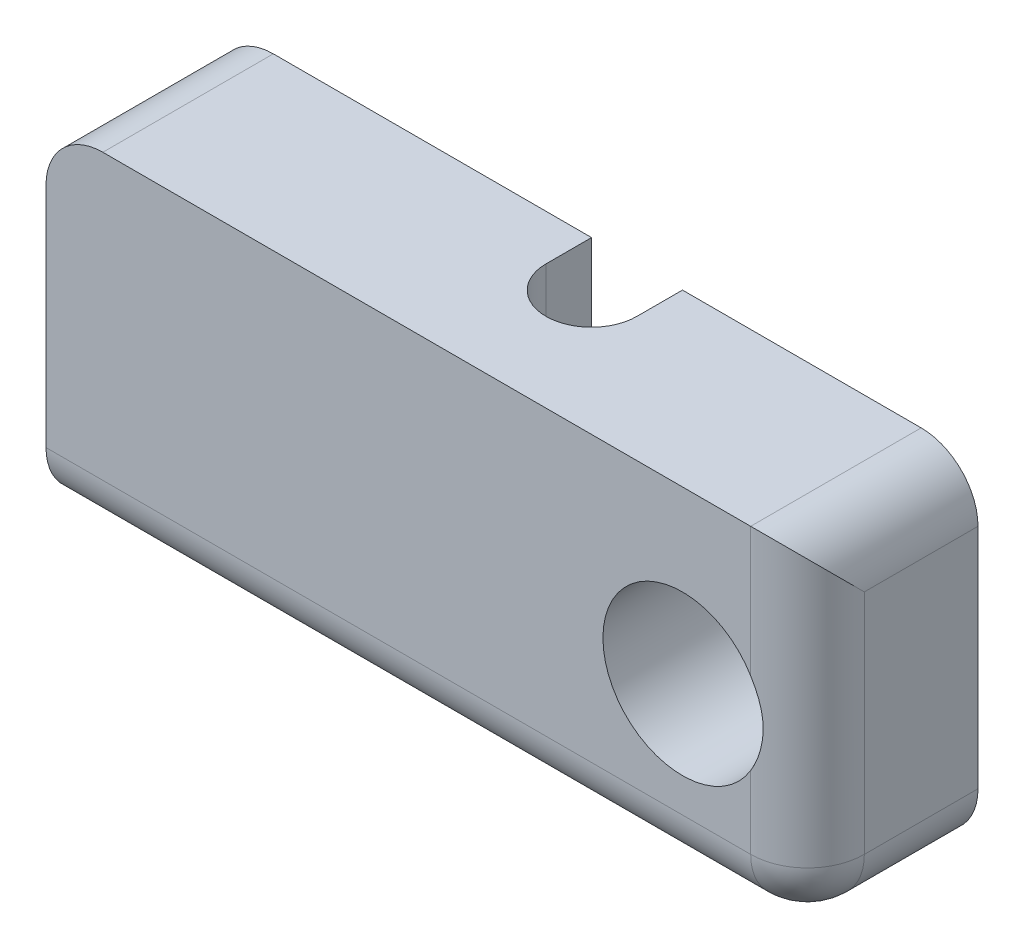
SolidWorks part; units mm, degrees
ref_plane "Front Plane" through (0, 0, 0) normal (0, 0, 1) x (1, 0, 0)
ref_plane "Top Plane" through (0, 0, 0) normal (0, 1, 0) x (1, 0, 0)
ref_plane "Right Plane" through (0, 0, 0) normal (1, 0, 0) x (0, 0, -1)
sketch "Sketch1" plane through (0, 0, 0) normal (0, 0, 1) x (1, 0, 0)
  line L0 (-34.2896, -7.3216) -> (-17.2716, -7.3216)
  line L1 (-34.2896, -7.3216) -> (-34.2896, -14.9416)
  line L2 (-17.2716, -7.3216) -> (-17.2716, -14.9416)
  line L3 (-34.2896, -14.9416) -> (-17.2716, -14.9416)
  line L4 (-34.2896, -8.5916) -> (-34.2896, -37.3677) construction
  line L5 (-17.2716, -13.6716) -> (-17.2716, -8.5916) construction
extrude "Boss-Extrude1" add sketch "Sketch1" along normal blind 3.81
fillet "Fillet1" radius 1.27 5 edges at (-17.2716, -11.1316, 3.81) (-25.7806, -14.9416, 3.81) (-34.2896, -7.3216, 1.905) (-17.2716, -7.3216, 1.905) (-17.2716, -14.9416, 1.905)
sketch "Sketch3" plane through (0, -14.9416, 0) normal (0, -1, 0) x (1, 0, 0)
  line L0 (-34.2896, 0) -> (-18.5416, 0) construction
  line L1 (-25.9076, 1.0185) -> (-25.9076, 0)
  line L2 (-23.8756, 1.0185) -> (-23.8756, 0)
  line L3 (-25.9076, 0) -> (-23.8756, 0)
  line L7 (-17.2716, 2.54) -> (-17.2716, 0) construction
  circle A0 centre (-24.8916, 1.0185) radius 1.016
  line M3 (-34.2896, 2.54) -> (-34.2896, 0)
  line M4 (-34.2896, 0) -> (-18.5416, 0)
  dimension "D1" = 7.62
  dimension "D2" = 2.032
extrude "Cut-Extrude8" cut sketch "Sketch3" against normal up to next contours A0 L1 L2 M4 | A0 M3
sketch "Sketch4" plane through (0, 0, 3.81) normal (0, 0, 1) x (1, 0, 0)
  circle A0 centre (-20.0656, -11.1316) radius 1.778 construction
  circle A1 centre (-20.0656, -11.1316) radius 1.778
extrude "Cut-Extrude9" cut sketch "Sketch4" against normal up to next
